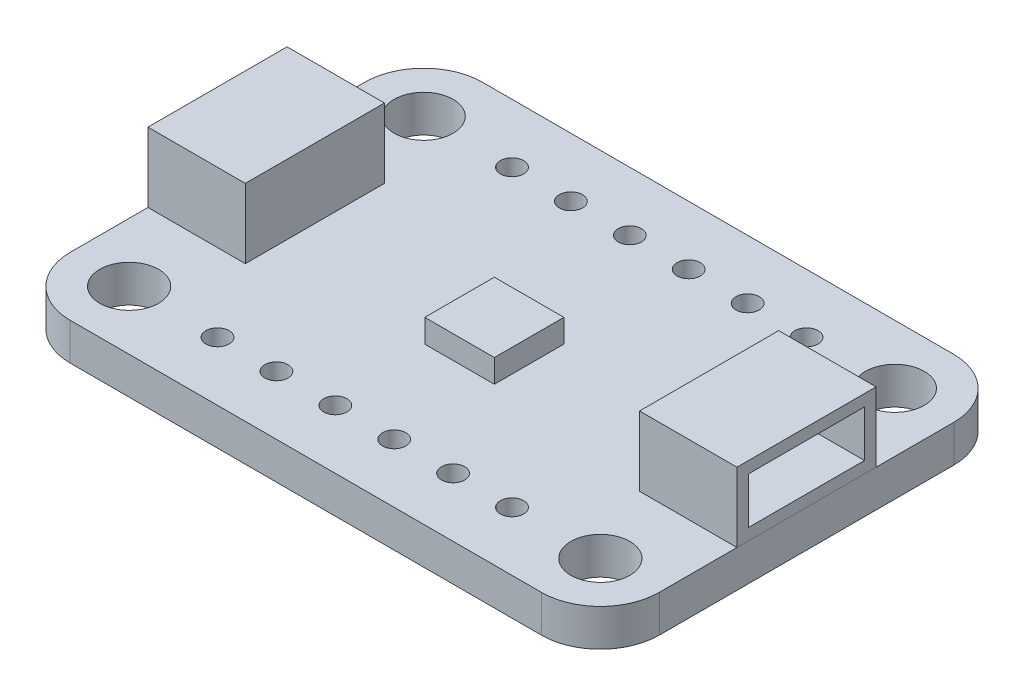
SolidWorks part; units mm, degrees
ref_plane "Front Plane" through (0, 0, 0) normal (0, 0, 1) x (1, 0, 0)
ref_plane "Top Plane" through (0, 0, 0) normal (0, 1, 0) x (1, 0, 0)
ref_plane "Right Plane" through (0, 0, 0) normal (1, 0, 0) x (0, 0, -1)
sketch "Sketch1" plane through (0, 0, 0) normal (0, 1, 0) x (1, 0, 0)
  line L0 (0, 8.89) -> (0, -8.89) construction
  line L1 (-10.16, 8.89) -> (10.16, 8.89)
  line L2 (-12.7, 6.35) -> (-12.7, -6.35)
  line L3 (-10.16, -8.89) -> (10.16, -8.89)
  line L4 (12.7, 6.35) -> (12.7, -6.35)
  line L5 (-12.7, 0) -> (12.7, 0) construction
  line L6 (-1.627, -0.635) -> (1.373, -0.635) construction
  line L7 (-1.627, 0.865) -> (1.373, 0.865) construction
  line L8 (-6.85, -6.35) -> (-6.35, -6.35) construction
  line L9 (-6.35, -6.35) -> (-3.81, -6.35) construction
  line L10 (-1.27, -6.35) -> (1.27, -6.35) construction
  line L11 (-3.81, -6.35) -> (-1.27, -6.35) construction
  line L12 (-1.627, 0.865) -> (-1.627, -2.135) construction
  line L13 (-1.627, -2.135) -> (1.373, -2.135) construction
  line L14 (1.373, 0.865) -> (1.373, -2.135) construction
  circle A0 centre (-10.16, 6.35) radius 1.27
  circle A1 centre (10.16, 6.35) radius 1.27
  arc A4 (10.16, 8.89) -> (12.7, 6.35) centre (10.16, 6.35) cw
  arc A5 (10.16, -8.89) -> (12.7, -6.35) centre (10.16, -6.35) ccw
  arc A6 (-12.7, -6.35) -> (-10.16, -8.89) centre (-10.16, -6.35) ccw
  arc A7 (-10.16, 8.89) -> (-12.7, 6.35) centre (-10.16, 6.35) ccw
  circle A14 centre (-1.27, -6.35) radius 0.5
  circle A15 centre (-3.81, -6.35) radius 0.5
  circle A16 centre (-6.35, -6.35) radius 0.5
  circle A20 centre (1.27, -6.35) radius 0.5
  circle A24 centre (3.81, -6.35) radius 0.5
  circle A25 centre (6.35, -6.35) radius 0.5
  circle A26 centre (6.35, 6.35) radius 0.5
  circle A27 centre (3.81, 6.35) radius 0.5
  circle A28 centre (1.27, 6.35) radius 0.5
  circle A29 centre (-1.27, 6.35) radius 0.5
  circle A30 centre (-3.81, 6.35) radius 0.5
  circle A31 centre (-6.35, 6.35) radius 0.5
  circle A32 centre (10.16, -6.35) radius 1.27
  circle A33 centre (-10.16, -6.35) radius 1.27
  point P51 (-0.127, -0.635)
  dimension "D1" = 25.4
  dimension "D3" = 2.54
  dimension "D5" = 1
  dimension "D2" = 17.78
  dimension "D4" = 2.54
  dimension "D6" = 3
  dimension "D7" = 12.573
  dimension "D8" = 8.255
  dimension "D9" = 0.127
  dimension "D10" = 0.635
  dimension "D11" = 2.54
extrude "Boss-Extrude1" add sketch "Sketch1" along normal blind 1.6
sketch "Sketch2" plane through (0, 1.6, 0) normal (0, 1, 0) x (1, 0, 0)
  line L0 (-1.627, 0.865) -> (1.373, 0.865) construction
  line L5 (-1.627, 0.865) -> (-1.627, -2.135) construction
  line L8 (-1.627, -2.135) -> (1.373, -2.135) construction
  line L9 (1.373, 0.865) -> (1.373, -2.135) construction
  line L10 (-1.627, 0.865) -> (1.373, 0.865)
  line L11 (-1.627, 0.865) -> (-1.627, -2.135)
  line L12 (-1.627, -2.135) -> (1.373, -2.135)
  line L13 (1.373, 0.865) -> (1.373, -2.135)
extrude "Boss-Extrude2" add sketch "Sketch2" along normal blind 1 separate body
sketch "Sketch3" plane through (0, 1.6, 0) normal (0, 1, 0) x (1, 0, 0)
  line L0 (-12.7, 0) -> (12.7, 0) construction
  line L1 (-12.7, 6.35) -> (-12.7, -6.35) construction
  line L2 (12.7, -6.35) -> (12.7, 6.35) construction
  line L3 (0, 8.89) -> (0, -8.89) construction
  line L4 (10.16, 8.89) -> (-10.16, 8.89) construction
  line L5 (-10.16, -8.89) -> (10.16, -8.89) construction
  line L6 (8.5, 3) -> (8.5, -3)
  line L7 (-12.7, 3) -> (-8.5, 3)
  line L8 (-12.7, 3) -> (-12.7, -3)
  line L9 (-12.7, -3) -> (-8.5, -3)
  line L10 (-8.5, 3) -> (-8.5, -3)
  line L11 (12.7, -3) -> (8.5, -3)
  line L12 (12.7, 3) -> (12.7, -3)
  line L13 (12.7, 3) -> (8.5, 3)
  dimension "D1" = 6
  dimension "D2" = 4.2
extrude "Boss-Extrude3" add sketch "Sketch3" along normal blind 3 separate body
shell "Shell1" thickness 0.5
shell "Shell2" thickness 0.5
